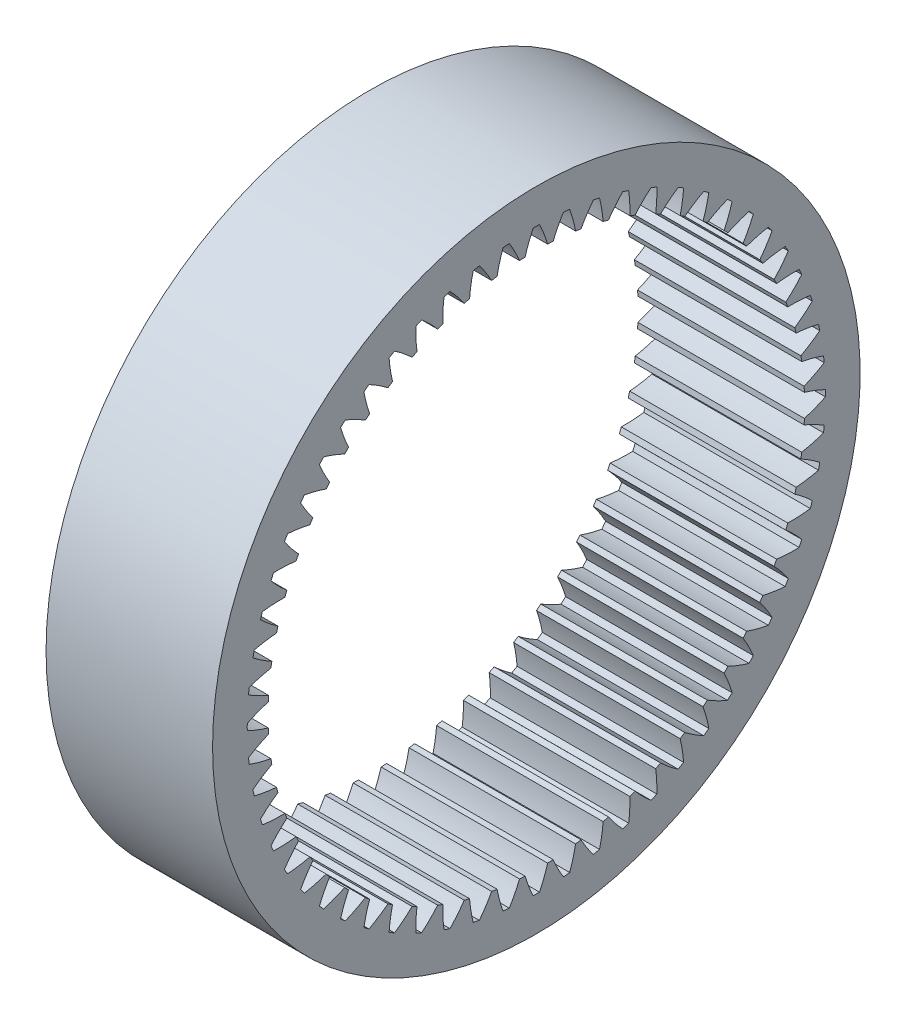
SolidWorks part; units mm, degrees
ref_plane "Plane1" through (0, 0, 0) normal (0, 0, 1) x (1, 0, 0)
ref_plane "Plane2" through (0, 0, 0) normal (0, 1, 0) x (1, 0, 0)
ref_plane "Plane3" through (0, 0, 0) normal (1, 0, 0) x (0, 0, -1)
other "Configuration Table"
sketch "HoldingSke" plane through (0, 0, 0) normal (0, 1, 0) x (1, 0, 0)
  line L0 (0, 0) -> (0.5, -0.866)
  line L1 (-15, 0) -> (100, 0) construction
  line L2 (0, 0) -> (-2.1039, 2.3779)
  line L3 (0, 0) -> (-11.863, 4.5341)
  line L4 (0, 0) -> (4.318, 7.479)
  line L5 (0, 0) -> (-23.7986, -8.8762)
  line L6 (0, 0) -> (-10.5278, -7.1032)
  line L7 (-2.1039, 2.3779) -> (3.3635, 27.1825)
  line L8 (-76.2, 3.3779) -> (-54.61, 3.3779)
  line L9 (-71.009, 38.7566) -> (-53.1078, 45.2721)
  line L10 (-76.2, 71.12) -> (104.1128, 71.12)
  line L11 (0, 0) -> (-18, 0)
  line L12 (-76.2, 101.6) -> (-76.162, 101.6)
  line L13 (24.9733, 27.94) -> (52.9518, 28.4284)
  line L14 (24.9733, 27.94) -> (24.9743, 27.94)
  line L15 (24.9733, 27.94) -> (100.4006, 29.5858)
  circle A0 centre (0, 0) radius 35
  circle A1 centre (0, 0) radius 12.7
  circle A2 centre (0, 0) radius 12.7
  dimension "MHD" = 25.4
  dimension "Hub_dia" = 25.4
  dimension "Diameter" = 70
  dimension "Num_teeth" = 60
  dimension "Pitch" = 1
  dimension "Overall_len" = 25.4
  dimension "Show_teeth" = 60
  dimension "Thickness" = 12.7
  dimension "OAL" = 25.4001
  dimension "T_dim" = 21.59
  dimension "Ap" = 20
  dimension "H" = 19.05
  dimension "Pitch_radius" = 180.3128
  dimension "Width" = 18
  dimension "Backlash" = 0.038
  dimension "Addendum_fac" = 1
  dimension "Dedendum_fac" = 1.25
  dimension "Clearance_fac" = 0.25
  dimension "Dedendum_add" = 0.001
  dimension "Module" = 1
sketch "BasProSke" plane through (0, 0, 0) normal (0, 1, 0) x (1, 0, 0)
  line L0 (-10, 0) -> (60, 0) construction
  line L1 (0, 29) -> (0, 35)
  line L2 (0, 29) -> (18, 29)
  line L3 (18, 29) -> (18, 35)
  line L4 (18, 35) -> (0, 35)
  dimension "Diameter" = 70
  dimension "Thickness" = 18
  dimension "Inside_diameter" = 58
revolve "Base-Revolve" add sketch "BasProSke" angle 360 about L0
sketch "TooCutSke" plane through (0, 0, 0) normal (1, 0, 0) x (0, 0, -1)
  line L3 (0.8803, 29.9871) -> (0.8803, 53.6633) construction
  line L4 (0, 0) -> (0, 59.563) construction
  line L5 (0, 0) -> (-3.576, 68.2339) construction
  line L6 (-13.1633, 24.7167) -> (36.4631, 27.3175) construction
  circle A0 centre (0, 0) radius 30 construction
  circle A1 centre (0, 0) radius 31.251 construction
  circle A2 centre (0, 0) radius 25.3717 construction
  circle A3 centre (0, 0) radius 28.9746 construction
  arc A4 (1.2274, 28.9486) -> (0.3395, 31.2492) centre (-13.1633, 24.7167) ccw
  arc A5 (1.2274, 28.9486) -> (-1.2274, 28.9486) centre (0, 0) ccw
  arc A6 (0.3395, 31.2492) -> (-0.3395, 31.2492) centre (0, 0) ccw
  arc A7 (-0.3395, 31.2492) -> (-1.2274, 28.9486) centre (13.1633, 24.7167) ccw
  dimension "Pitch_dia" = 60
  dimension "Base_dia" = 50.7434
  dimension "Root_dia" = 62.502
  dimension "Overcut_dia" = 57.9492
  dimension "Flank_rad" = 15
  dimension "Half_ang" = 3
  dimension "Half_CT" = 0.8803
extrude "ToothCut" cut sketch "TooCutSke" along normal through all
fillet "Breaks" [suppressed] radius 0.1
fillet "RootFillets" [suppressed] radius 0.251
pattern_circular "TeethCuts" count 60 every 6 about axis through (-10, 0, 0) along (1, 0, 0) of "RootFillets", "Breaks", "ToothCut"
equation "' \"Module@HoldingSke\" = 6.35"
equation "' \"Num_teeth@HoldingSke\" = 24"
equation "' \"Ap@HoldingSke\" =  14.5"
equation "' \"Ap@HoldingSke\" = 14.5"
equation "' \"Width@HoldingSke\" = 12"
equation "' \"Diameter@HoldingSke\" = 8 * 25.4"
equation "' \"Show_teeth@HoldingSke\" = 100"
equation "' \"Backlash@HoldingSke\" = 0.009 * 25.4"
equation "' \"Addendum_fac@HoldingSke\" = 1.0"
equation "' \"Dedendum_fac@HoldingSke\" = 1.25"
equation "' \"Dedendum_add@HoldingSke\" = 0.00005 * 25.4"
equation "' \"Clearance_fac@HoldingSke\" = 0.25"
equation "\"Pitch@HoldingSke\" = 1 / \"Module@HoldingSke\" "
equation "\"Overcut_dia@TooCutSke\" = (\"Num_teeth@HoldingSke\" - 2 * \"Addendum_fac@HoldingSke\") / \"Pitch@HoldingSke\" - 0.002 * 25.4"
equation "\"Pitch_dia@TooCutSke\" = \"Num_teeth@HoldingSke\" / \"Pitch@HoldingSke\""
equation "\"Base_dia@TooCutSke\" = \"Num_teeth@HoldingSke\" / \"Pitch@HoldingSke\" * cos((\"Ap@HoldingSke\"  * 3.14159265 / 180)) * 0.90"
equation "\"Root_dia@TooCutSke\" = \"Num_teeth@HoldingSke\"  / \"Pitch@HoldingSke\" + 2 *  \"Dedendum_fac@HoldingSke\"/ \"Pitch@HoldingSke\" + \"Dedendum_add@HoldingSke\" * 2"
equation "\"Half_ang@TooCutSke\" = 180 / \"Num_teeth@HoldingSke\""
equation "\"Half_CT@TooCutSke\" = \"Num_teeth@HoldingSke\" / \"Pitch@HoldingSke\" * sin((3.14159265 / 2 / \"Num_teeth@HoldingSke\")) / 2 + 10 * \"Backlash@HoldingSke\" / 4"
equation "\"Flank_rad@TooCutSke\" = \"Num_teeth@HoldingSke\" / \"Pitch@HoldingSke\" / 4"
equation "\"Radius@RootFillets\"= \"Clearance_fac@HoldingSke\" / \"Pitch@HoldingSke\" + \"Dedendum_add@HoldingSke\""
equation "\"Break_rad@Breaks\" = 0.02 / \"Pitch@HoldingSke\" * 5"
equation "\"Num_teeth@TeethCuts\" = int( \"Show_teeth@HoldingSke\" ) + 1"
equation "\"Num_teeth@TeethCuts\" = ((sgn( \"Num_teeth@TeethCuts\" - \"Num_teeth@HoldingSke\" )-1)*( \"Num_teeth@TeethCuts\" - \"Num_teeth@HoldingSke\" ))/-2+ \"Num_teeth@HoldingSke\""
equation "\"Num_teeth@TeethCuts\" = ((sgn( \"Num_teeth@TeethCuts\" - 2.0)+1)*( \"Num_teeth@TeethCuts\" - 2.0))/2 +2.0"
equation "\"Angle@TeethCuts\" = 360.0 / \"Num_teeth@HoldingSke\""
equation "\"Diameter@BasProSke\" = \"Num_teeth@HoldingSke\"  / \"Pitch@HoldingSke\" + 2 *  \"Dedendum_fac@HoldingSke\"/ \"Pitch@HoldingSke\" + \"Dedendum_add@HoldingSke\" * 2 + 0.002 * 25.4"
equation "\"Diameter@BasProSke\" = ((sgn( \"Diameter@BasProSke\"  - \"Diameter@HoldingSke\" )+1)*( \"Diameter@BasProSke\"  - \"Diameter@HoldingSke\" ))/2 + \"Diameter@HoldingSke\""
equation "\"Inside_diameter@BasProSke\" =  (\"Num_teeth@HoldingSke\" - 2 * \"Addendum_fac@HoldingSke\") / \"Pitch@HoldingSke\" "
equation "\"Thickness@BasProSke\"  = \"Width@HoldingSke\""
